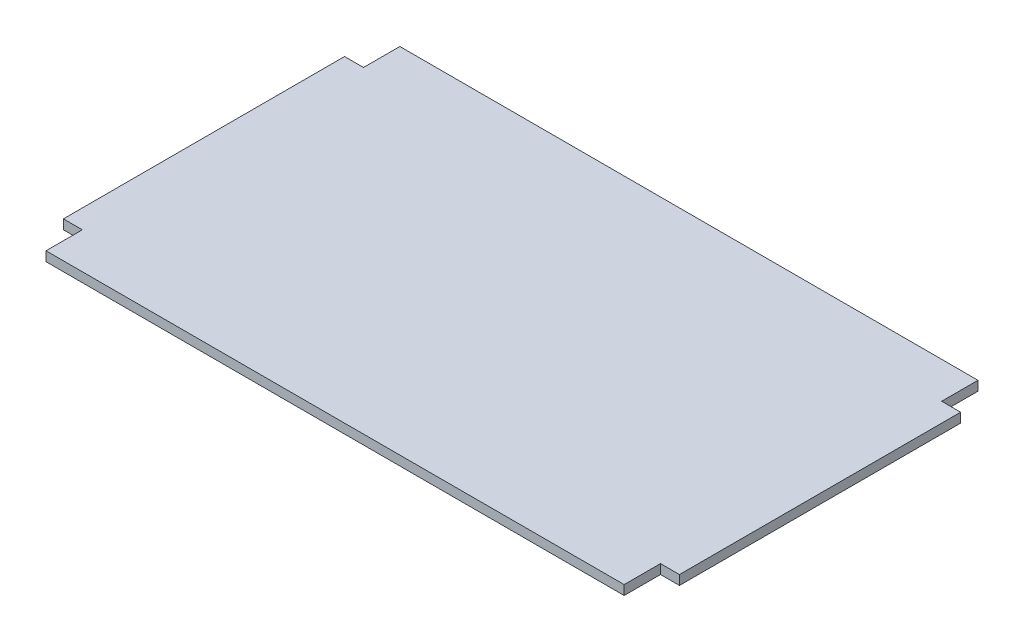
SolidWorks part; units mm, degrees
material "Balsa"
ref_plane "Front Plane" through (0, 0, 0) normal (0, 0, 1) x (1, 0, 0)
ref_plane "Top Plane" through (0, 0, 0) normal (0, 1, 0) x (1, 0, 0)
ref_plane "Right Plane" through (0, 0, 0) normal (1, 0, 0) x (0, 0, -1)
sketch "Sketch1" plane through (0, 0, 0) normal (0, 1, 0) x (1, 0, 0)
  line L0 (1238.25, 0) -> (1200.15, 0)
  line L1 (38.1, 73.025) -> (1200.15, 73.025)
  line L2 (0, 0) -> (0, -565.15)
  line L3 (38.1, -638.175) -> (1200.15, -638.175)
  line L4 (1238.25, 0) -> (1238.25, -565.15)
  line L5 (1200.15, 0) -> (1200.15, 73.025)
  line L6 (1238.25, -565.15) -> (1200.15, -565.15)
  line L7 (1200.15, -565.15) -> (1200.15, -638.175)
  line L8 (0, 0) -> (38.1, 0)
  line L9 (38.1, 0) -> (38.1, 73.025)
  line L10 (38.1, -638.175) -> (38.1, -565.15)
  line L11 (38.1, -565.15) -> (0, -565.15)
  dimension "D2" = 73.025
  dimension "D3" = 38.1
  dimension "D4" = 73.025
  dimension "D5" = 38.1
  dimension "D6" = 38.1
  dimension "D7" = 38.1
  dimension "D8" = 73.025
  dimension "D9" = 73.025
  dimension "D10" = 1162.05
  dimension "D11" = 565.15
extrude "Boss-Extrude1" add sketch "Sketch1" along normal blind 19.05
sketch "Sketch2" plane through (0, 0, 638.175) normal (0, 0, 1) x (1, 0, 0)
  line L0 (1238.25, 19.05) -> (1238.25, 0) construction
  line L1 (38.1, 0) -> (1200.15, 0) construction
  line L2 (0, 19.05) -> (0, 0) construction
  circle A0 centre (19.05, 9.525) radius 3.175
  circle A1 centre (1219.2, 9.525) radius 3.175
  dimension "D1" = 6.35
  dimension "D2" = 6.35
  dimension "D3" = 19.05
  dimension "D4" = 9.525
  dimension "D5" = 19.05
  dimension "D6" = 9.525
ref_plane "Plane1" through (0, 0, 282.575) normal (0, 0, 1) x (1, 0, 0)
ref_plane "Plane2" through (619.125, 0, 0) normal (-1, 0, 0) x (0, 0, 1)
sketch "Sketch3" plane through (38.1, 0, 0) normal (-1, 0, 0) x (0, 0, 1)
  line L1 (638.175, 19.05) -> (638.175, 0) construction
  line L2 (565.15, 19.05) -> (638.175, 19.05) construction
  line L3 (-73.025, 19.05) -> (-73.025, 0) construction
  line L4 (-73.025, 19.05) -> (0, 19.05) construction
  circle A0 centre (625.475, 9.525) radius 3.175
  circle A1 centre (-60.325, 9.525) radius 3.175
  dimension "D1" = 6.35
  dimension "D2" = 12.7
  dimension "D3" = 9.525
  dimension "D4" = 6.35
  dimension "D5" = 12.7
  dimension "D6" = 9.525
